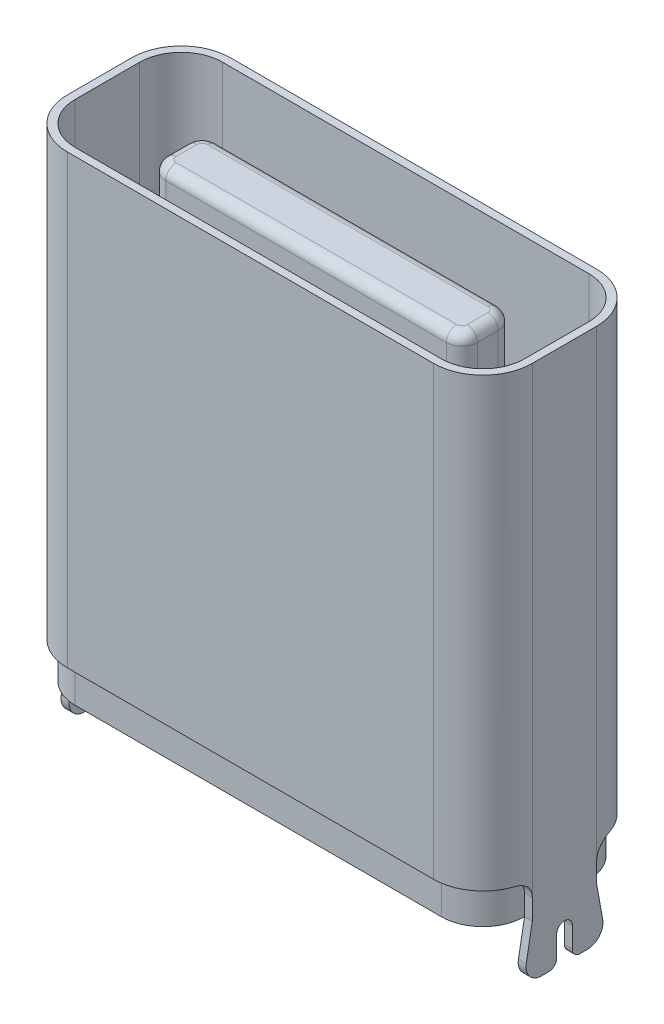
SolidWorks part; units mm, degrees
ref_plane "Front Plane" through (0, 0, 0) normal (0, 0, 1) x (1, 0, 0)
ref_plane "Top Plane" through (0, 0, 0) normal (0, 1, 0) x (1, 0, 0)
ref_plane "Right Plane" through (0, 0, 0) normal (1, 0, 0) x (0, 0, -1)
sketch "草图1" plane through (0, 0, 0) normal (0, 1, 0) x (1, 0, 0)
  line L0 (0.8, 0) -> (7.85, 0)
  line L1 (8.65, 0.8) -> (8.65, 2.04)
  line L2 (7.85, 2.84) -> (0.8, 2.84)
  line L3 (0, 2.04) -> (0, 0.8)
  line L8 (0.8, -0.15) -> (7.85, -0.15)
  line L9 (8.8, 0.8) -> (8.8, 2.04)
  line L10 (7.85, 2.99) -> (0.8, 2.99)
  line L11 (-0.15, 2.04) -> (-0.15, 0.8)
  arc A0 (7.85, 0) -> (8.65, 0.8) centre (7.85, 0.8) ccw
  arc A1 (8.65, 2.04) -> (7.85, 2.84) centre (7.85, 2.04) ccw
  arc A2 (0.8, 0) -> (0, 0.8) centre (0.8, 0.8) cw
  arc A3 (0.8, 2.84) -> (0, 2.04) centre (0.8, 2.04) ccw
  arc A8 (7.85, -0.15) -> (8.8, 0.8) centre (7.85, 0.8) ccw
  arc A9 (8.8, 2.04) -> (7.85, 2.99) centre (7.85, 2.04) ccw
  arc A10 (0.8, 2.99) -> (-0.15, 2.04) centre (0.8, 2.04) ccw
  arc A11 (0.8, -0.15) -> (-0.15, 0.8) centre (0.8, 0.8) cw
  point P11 (0, 0)
  dimension "D1" = 0.8
  dimension "D2" = 0.15
extrude "凸台-拉伸1" add sketch "草图1" along normal blind 9.3
sketch "草图3" plane through (-0.15, 0, 0) normal (-1, 0, 0) x (0, 0, 1)
  line L0 (-2.04, 0) -> (-0.8, 0)
  line L2 (-1.12, -1) -> (-0.9788, -1)
  line L3 (-0.6836, -0.6469) -> (-0.8, 0)
  line L4 (-1.72, -1) -> (-1.8612, -1)
  line L5 (-2.1564, -0.6469) -> (-2.04, 0)
  line L7 (-1.57, -0.45) -> (-1.57, -0.85)
  line L9 (-1.27, -0.85) -> (-1.27, -0.45)
  arc A0 (-0.9788, -1) -> (-0.6836, -0.6469) centre (-0.9788, -0.7) ccw
  arc A1 (-1.8612, -1) -> (-2.1564, -0.6469) centre (-1.8612, -0.7) cw
  arc A2 (-1.12, -1) -> (-1.27, -0.85) centre (-1.12, -0.85) cw
  arc A3 (-1.57, -0.85) -> (-1.72, -1) centre (-1.72, -0.85) cw
  arc A4 (-1.42, -0.3) -> (-1.57, -0.45) centre (-1.42, -0.45) ccw
  arc A5 (-1.27, -0.45) -> (-1.42, -0.3) centre (-1.42, -0.45) ccw
  dimension "D1" = 0.3
  dimension "D2" = 0.15
extrude "凸台-拉伸2" add sketch "草图3" against normal blind 0.15
sketch "草图4" plane through (8.8, 0, 0) normal (1, 0, 0) x (0, 0, -1)
  line L0 (0.8, 0) -> (2.04, 0) construction
  line L1 (0.6836, -0.6469) -> (0.8, 0) construction
  line L2 (1.12, -1) -> (0.9788, -1) construction
  line L3 (1.27, -0.45) -> (1.27, -0.85) construction
  line L4 (1.57, -0.85) -> (1.57, -0.45) construction
  line L5 (1.8612, -1) -> (1.72, -1) construction
  line L6 (2.04, 0) -> (2.1564, -0.6469) construction
  line L7 (0.8, 0) -> (2.04, 0)
  line L8 (0.6836, -0.6469) -> (0.8, 0)
  line L9 (1.12, -1) -> (0.9788, -1)
  line L10 (1.27, -0.45) -> (1.27, -0.85)
  line L11 (1.57, -0.85) -> (1.57, -0.45)
  line L12 (1.8612, -1) -> (1.72, -1)
  line L13 (2.04, 0) -> (2.1564, -0.6469)
  arc A0 (0.6836, -0.6469) -> (0.9788, -1) centre (0.9788, -0.7) ccw construction
  arc A1 (1.12, -1) -> (1.27, -0.85) centre (1.12, -0.85) ccw construction
  arc A2 (1.57, -0.45) -> (1.27, -0.45) centre (1.42, -0.45) ccw construction
  arc A3 (1.57, -0.85) -> (1.72, -1) centre (1.72, -0.85) ccw construction
  arc A4 (1.8612, -1) -> (2.1564, -0.6469) centre (1.8612, -0.7) ccw construction
  arc A5 (0.6836, -0.6469) -> (0.9788, -1) centre (0.9788, -0.7) ccw
  arc A6 (1.12, -1) -> (1.27, -0.85) centre (1.12, -0.85) ccw
  arc A7 (1.57, -0.45) -> (1.27, -0.45) centre (1.42, -0.45) ccw
  arc A8 (1.57, -0.85) -> (1.72, -1) centre (1.72, -0.85) ccw
  arc A9 (1.8612, -1) -> (2.1564, -0.6469) centre (1.8612, -0.7) ccw
extrude "凸台-拉伸3" add sketch "草图4" against normal blind 0.15
sketch "草图5" plane through (0, 0, 0) normal (0, -1, 0) x (1, 0, 0)
  line L3 (0.8, -2.99) -> (7.85, -2.99) construction
  line L5 (7.85, 0.15) -> (0.8, 0.15) construction
  line L11 (0.8, -2.99) -> (7.85, -2.99)
  line L13 (7.85, 0.15) -> (0.8, 0.15)
  line L18 (8.8, -0.8) -> (8.8, -2.04)
  line L19 (-0.15, -0.8) -> (-0.15, -2.04)
  arc A2 (-0.15, -2.04) -> (0.8, -2.99) centre (0.8, -2.04) ccw construction
  arc A3 (7.85, -2.99) -> (8.8, -2.04) centre (7.85, -2.04) ccw construction
  arc A4 (8.8, -0.8) -> (7.85, 0.15) centre (7.85, -0.8) ccw construction
  arc A5 (0.8, 0.15) -> (-0.15, -0.8) centre (0.8, -0.8) ccw construction
  arc A10 (-0.15, -2.04) -> (0.8, -2.99) centre (0.8, -2.04) ccw
  arc A11 (7.85, -2.99) -> (8.8, -2.04) centre (7.85, -2.04) ccw
  arc A12 (8.8, -0.8) -> (7.85, 0.15) centre (7.85, -0.8) ccw
  arc A13 (0.8, 0.15) -> (-0.15, -0.8) centre (0.8, -0.8) ccw
extrude "凸台-拉伸4" add sketch "草图5" against normal blind 2
sketch "草图6" plane through (0, 0, 0) normal (0, -1, 0) x (1, 0, 0)
  line L4 (0.8, 0.15) -> (7.85, 0.15) construction
  line L5 (7.85, -2.99) -> (0.8, -2.99) construction
  line L6 (0.8, 0.15) -> (7.85, 0.15)
  line L7 (7.85, -2.99) -> (0.8, -2.99)
  line L14 (7.85, -2.84) -> (0.8, -2.84)
  line L15 (0.8, 0) -> (7.85, 0)
  line L21 (0, -0.8) -> (-0.15, -0.8) construction
  line L22 (0, -0.8) -> (-0.15, -0.8)
  line L23 (8.65, -0.8) -> (8.8, -0.8) construction
  line L24 (8.65, -0.8) -> (8.8, -0.8)
  line L25 (8.65, -2.04) -> (8.8, -2.04) construction
  line L26 (8.65, -2.04) -> (8.8, -2.04)
  line L27 (0, -2.04) -> (-0.15, -2.04) construction
  line L28 (0, -2.04) -> (-0.15, -2.04)
  line L33 (0.0141, -2.1893) -> (0.0141, -2.1893) construction
  line L34 (8.6359, -2.1893) -> (8.6359, -2.1893) construction
  line L35 (0.0141, -0.6507) -> (0.0141, -0.6507) construction
  line L36 (8.6359, -0.6507) -> (8.6359, -0.6507) construction
  arc A4 (0.8, 0.15) -> (-0.15, -0.8) centre (0.8, -0.8) ccw construction
  arc A5 (8.8, -0.8) -> (7.85, 0.15) centre (7.85, -0.8) ccw construction
  arc A6 (7.85, -2.99) -> (8.8, -2.04) centre (7.85, -2.04) ccw construction
  arc A7 (-0.15, -2.04) -> (0.8, -2.99) centre (0.8, -2.04) ccw construction
  arc A12 (0.8, 0.15) -> (-0.15, -0.8) centre (0.8, -0.8) ccw
  arc A13 (8.8, -0.8) -> (7.85, 0.15) centre (7.85, -0.8) ccw
  arc A14 (7.85, -2.99) -> (8.8, -2.04) centre (7.85, -2.04) ccw
  arc A15 (-0.15, -2.04) -> (0.8, -2.99) centre (0.8, -2.04) ccw
  arc A16 (7.85, 0) -> (8.65, -0.8) centre (7.85, -0.8) cw
  arc A17 (0.8, 0) -> (0, -0.8) centre (0.8, -0.8) ccw
  arc A18 (0.0141, -2.1893) -> (0.8, -2.84) centre (0.8, -2.04) ccw construction
  arc A19 (7.85, -2.84) -> (8.6359, -2.1893) centre (7.85, -2.04) ccw construction
  arc A20 (0.8, 0) -> (0.0141, -0.6507) centre (0.8, -0.8) ccw construction
  arc A21 (8.6359, -0.6507) -> (7.85, 0) centre (7.85, -0.8) ccw construction
  arc A22 (0.8, -2.84) -> (0, -2.04) centre (0.8, -2.04) cw
  arc A23 (7.85, -2.84) -> (8.65, -2.04) centre (7.85, -2.04) ccw
  dimension "D1" = 0.15
  dimension "D2" = 0.15
extrude "切除-拉伸1" cut sketch "草图6" against normal blind 0.7
fillet "圆角1" radius 0.3 4 edges at (8.725, 0.7, -0.8) (8.725, 0.7, -2.04) (-0.075, 0.7, -2.04) (-0.075, 0.7, -0.8)
sketch "草图7" plane through (0, 0, -2.99) normal (0, 0, -1) x (-1, 0, 0)
  line L0 (-3.225, 0.7) -> (-5.425, 0.7)
  line L4 (-4.325, -1.2) -> (-4.625, -1.2)
  line L5 (-4.925, -0.9) -> (-4.925, 0.2)
  line L6 (-4.325, -1.2) -> (-4.025, -1.2)
  line L7 (-3.725, -0.9) -> (-3.725, 0.2)
  arc A0 (-4.925, 0.2) -> (-5.425, 0.7) centre (-5.425, 0.2) ccw
  arc A1 (-3.225, 0.7) -> (-3.725, 0.2) centre (-3.225, 0.2) ccw
  arc A2 (-4.025, -1.2) -> (-3.725, -0.9) centre (-4.025, -0.9) ccw
  arc A3 (-4.625, -1.2) -> (-4.925, -0.9) centre (-4.625, -0.9) cw
  dimension "D1" = 0.5
  dimension "D2" = 0.5
  dimension "D3" = 0.3
extrude "凸台-拉伸5" add sketch "草图7" against normal blind 0.15
sketch "草图8" plane through (0, 0, -2.99) normal (0, 0, -1) x (-1, 0, 0)
  line L2 (-4.325, -0.9) -> (-4.125, -0.9)
  line L3 (-4.025, -0.8) -> (-4.025, -0.4)
  line L4 (-4.125, -0.3) -> (-4.525, -0.3)
  line L5 (-4.625, -0.4) -> (-4.625, -0.8)
  line L6 (-4.525, -0.9) -> (-4.325, -0.9)
  arc A0 (-4.025, -0.4) -> (-4.125, -0.3) centre (-4.125, -0.4) ccw
  arc A1 (-4.125, -0.9) -> (-4.025, -0.8) centre (-4.125, -0.8) ccw
  arc A2 (-4.625, -0.8) -> (-4.525, -0.9) centre (-4.525, -0.8) ccw
  arc A3 (-4.525, -0.3) -> (-4.625, -0.4) centre (-4.525, -0.4) ccw
  dimension "D1" = 0.1
extrude "切除-拉伸2" cut sketch "草图8" against normal blind 0.15
sketch "草图9" plane through (0, 2, 0) normal (0, 1, 0) x (1, 0, 0)
  line L3 (1.325, 1.42) -> (1.325, 1.62)
  line L4 (1.625, 1.92) -> (7.025, 1.92)
  line L5 (7.325, 1.62) -> (7.325, 1.22)
  line L6 (7.025, 0.92) -> (1.625, 0.92)
  line L7 (1.325, 1.22) -> (1.325, 1.42)
  arc A0 (7.025, 1.92) -> (7.325, 1.62) centre (7.025, 1.62) cw
  arc A1 (7.325, 1.22) -> (7.025, 0.92) centre (7.025, 1.22) cw
  arc A2 (1.625, 0.92) -> (1.325, 1.22) centre (1.625, 1.22) cw
  arc A3 (1.325, 1.62) -> (1.625, 1.92) centre (1.625, 1.62) cw
  dimension "D1" = 0.3
extrude "凸台-拉伸6" add sketch "草图9" along normal offset from surface 0.4 up to face at (4.325, 9.3, -1.42)
fillet "圆角2" radius 0.2 8 edges at (7.2371, 8.9, -1.8321) (7.325, 8.9, -1.42) (7.2371, 8.9, -1.0079) (4.325, 8.9, -0.92) (1.4129, 8.9, -1.0079) (1.325, 8.9, -1.42) (1.4129, 8.9, -1.8321) (4.325, 8.9, -1.92)
